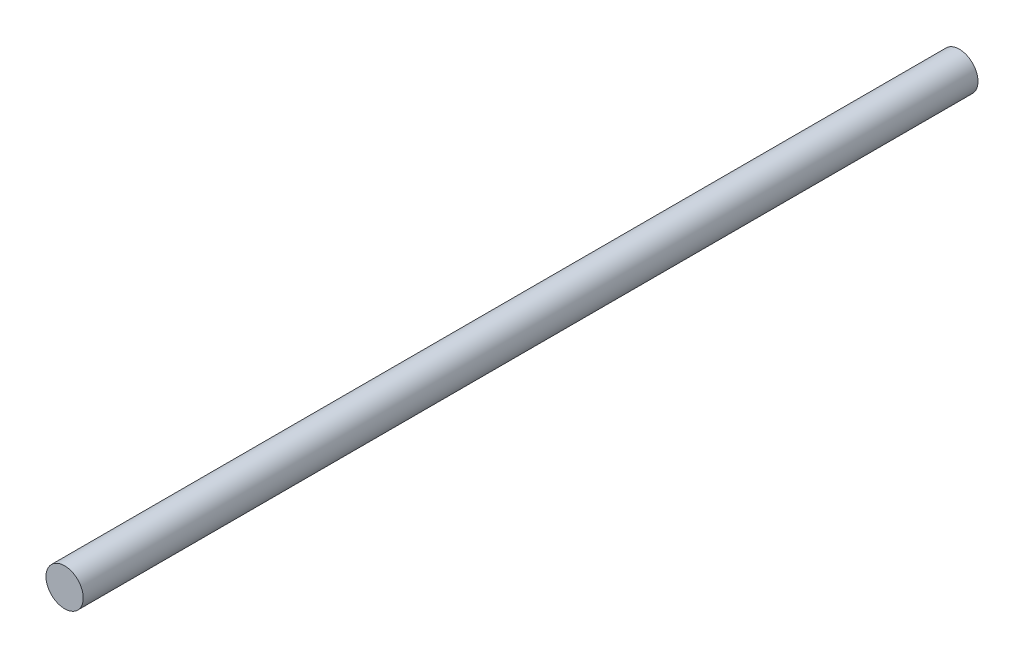
SolidWorks part; units mm, degrees
ref_plane "Front Plane" through (0, 0, 0) normal (0, 0, 1) x (1, 0, 0)
ref_plane "Top Plane" through (0, 0, 0) normal (0, 1, 0) x (1, 0, 0)
ref_plane "Right Plane" through (0, 0, 0) normal (1, 0, 0) x (0, 0, -1)
other "Configuration Table"
sketch "Sketch1" plane through (0, 0, 0) normal (0, 0, 1) x (1, 0, 0)
  circle A0 centre (0, 0) radius 2.5
extrude "KABLO_24V_D5x120" add sketch "Sketch1" against normal blind 120 separate body
